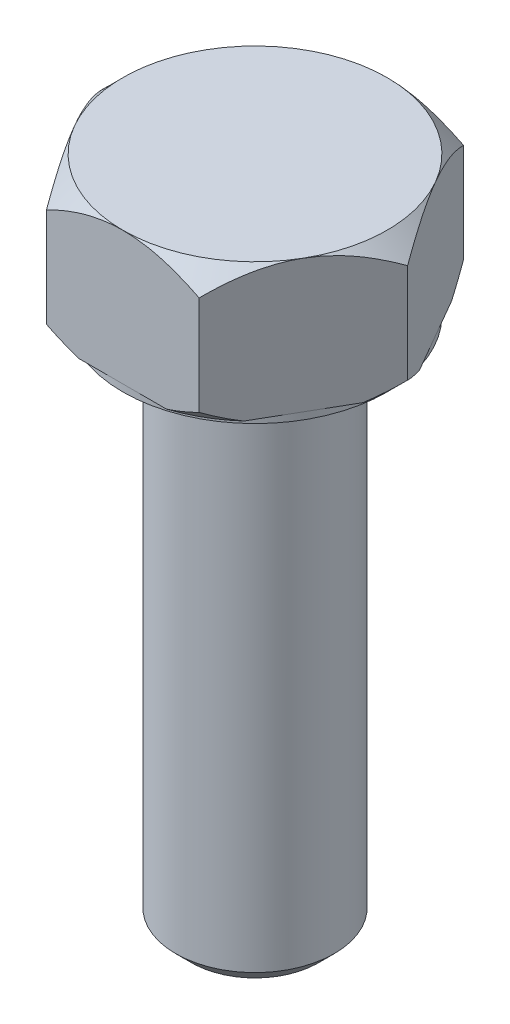
SolidWorks part; units mm, degrees
material "Cast Stainless Steel"
ref_plane "Front Plane" through (0, 0, 0) normal (0, 0, 1) x (1, 0, 0)
ref_plane "Top Plane" through (0, 0, 0) normal (0, 1, 0) x (1, 0, 0)
ref_plane "Right Plane" through (0, 0, 0) normal (1, 0, 0) x (0, 0, -1)
sketch "Sketch1" plane through (0, 0, 0) normal (0, 1, 0) x (1, 0, 0)
  line L0 (0, 0) -> (5.7735, 0) construction
  line L1 (5.7735, 0) -> (2.8868, 5)
  line L2 (2.8868, 5) -> (-2.8868, 5)
  line L3 (-2.8868, 5) -> (-5.7735, 0)
  line L4 (-5.7735, 0) -> (-2.8868, -5)
  line L5 (-2.8868, -5) -> (2.8868, -5)
  line L6 (2.8868, -5) -> (5.7735, 0)
  circle A0 centre (0, 0) radius 5 construction
  dimension "D1" = 10
extrude "Boss-Extrude1" add sketch "Sketch1" against normal blind 5.3
sketch "Sketch4" plane through (0, 0, 0) normal (1, 0, 0) x (0, 0, -1)
  line L0 (-5, 0) -> (-6.65, 0)
  line L1 (-6.65, 0) -> (-6.65, -1.65)
  line L2 (-6.65, -1.65) -> (-5, 0)
  line L3 (-5, -2.65) -> (5, -2.65) construction
  line L4 (-6.65, -3.65) -> (-5, -5.3)
  line L5 (-6.65, -5.3) -> (-6.65, -3.65)
  line L6 (-5, -5.3) -> (-6.65, -5.3)
  line L7 (0, 0) -> (0, -2.65) construction
  dimension "D1" = 45
  dimension "D2" = 2.65
  dimension "D3" = 1.65
  dimension "D4" = 10
revolve "Cut-Revolve1" cut sketch "Sketch4" angle 360 about L7
sketch "Sketch2" plane through (0, -5.3, 0) normal (0, -1, 0) x (1, 0, 0)
  circle A0 centre (0, 0) radius 5
  dimension "D1" = 10
extrude "Cut-Extrude1" cut sketch "Sketch2" against normal blind 0.265 flip side to cut
sketch "Sketch3" plane through (0, -5.3, 0) normal (0, -1, 0) x (1, 0, 0)
  circle A0 centre (0, 0) radius 3
  dimension "D1" = 6
extrude "Boss-Extrude2" add sketch "Sketch3" along normal blind 20
chamfer "Chamfer1" distance 0.6 angle 45 1 edges at (0, -25.3, -3)
equation "\"k\"= 5.3"
equation "\"e\"= 14.38"
equation "\"S\"=10"
equation "\"L\"= 20"
equation "\"D1@Sketch1\"=\"S\""
equation "\"D1@Boss-Extrude1\"=\"k\""
equation "\"D1@Sketch2\"=\"S\""
equation "\"D1@Cut-Extrude1\"=\"k\"/20"
equation "\"d\"=6"
equation "\"D1@Sketch3\"=\"d\""
equation "\"D1@Boss-Extrude2\"=\"L\""
equation "\"D2@Sketch4\"=\"k\"/2"
equation "\"D3@Sketch4\"=\"D2@Sketch4\"-1"
equation "\"D4@Sketch4\"=\"S\""
equation "\"D1@Chamfer1\"=\"d\"/10"
